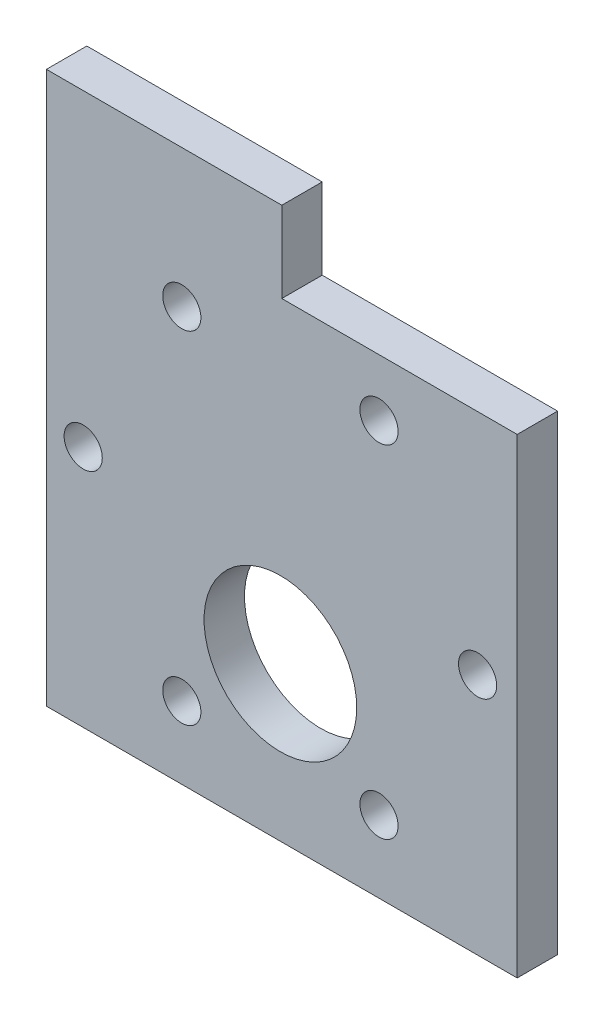
SolidWorks part; units mm, degrees
ref_plane "Front Plane" through (0, 0, 0) normal (0, 0, 1) x (1, 0, 0)
ref_plane "Top Plane" through (0, 0, 0) normal (0, 1, 0) x (1, 0, 0)
ref_plane "Right Plane" through (0, 0, 0) normal (1, 0, 0) x (0, 0, -1)
sketch "Sketch1" plane through (0, 0, 0) normal (0, 0, 1) x (1, 0, 0)
  line L1 (18.5, 0) -> (37, 0)
  line L2 (0, 0) -> (0, 37)
  line L3 (18.5, 37) -> (37, 37)
  line L4 (37, 0) -> (37, 37)
  line L7 (18.5, 0) -> (0, 0)
  line L8 (18.5, 0) -> (18.5, 11.35) construction
  line L9 (18.5, 37) -> (18.5, 43.35)
  line L10 (37, 0) -> (0, 37) construction
  line L11 (18.5, 43.35) -> (0, 43.35)
  line L12 (0, 43.35) -> (0, 37)
  line L14 (18.5, 37) -> (0, 37) construction
  circle A1 centre (18.3902, 12.0899) radius 6 construction
  circle A2 centre (18.3902, 12.0899) radius 6
  circle A3 centre (2.8902, 19.0899) radius 1.5 construction
  circle A4 centre (2.8902, 19.0899) radius 1.5
  circle A5 centre (10.6402, 5.6665) radius 1.5 construction
  circle A6 centre (10.6402, 5.6665) radius 1.5
  circle A7 centre (26.1402, 5.6665) radius 1.5 construction
  circle A8 centre (26.1402, 5.6665) radius 1.5
  circle A9 centre (33.8902, 19.0899) radius 1.5 construction
  circle A10 centre (33.8902, 19.0899) radius 1.5
  circle A11 centre (26.1402, 32.5133) radius 1.5 construction
  circle A12 centre (26.1402, 32.5133) radius 1.5
  circle A13 centre (10.6402, 32.5133) radius 1.5 construction
  circle A14 centre (10.6402, 32.5133) radius 1.5
  dimension "D1" = 37
  dimension "D2" = 37
  dimension "D3" = 6.35
extrude "Boss-Extrude1" add sketch "Sketch1" along normal blind 3.175
